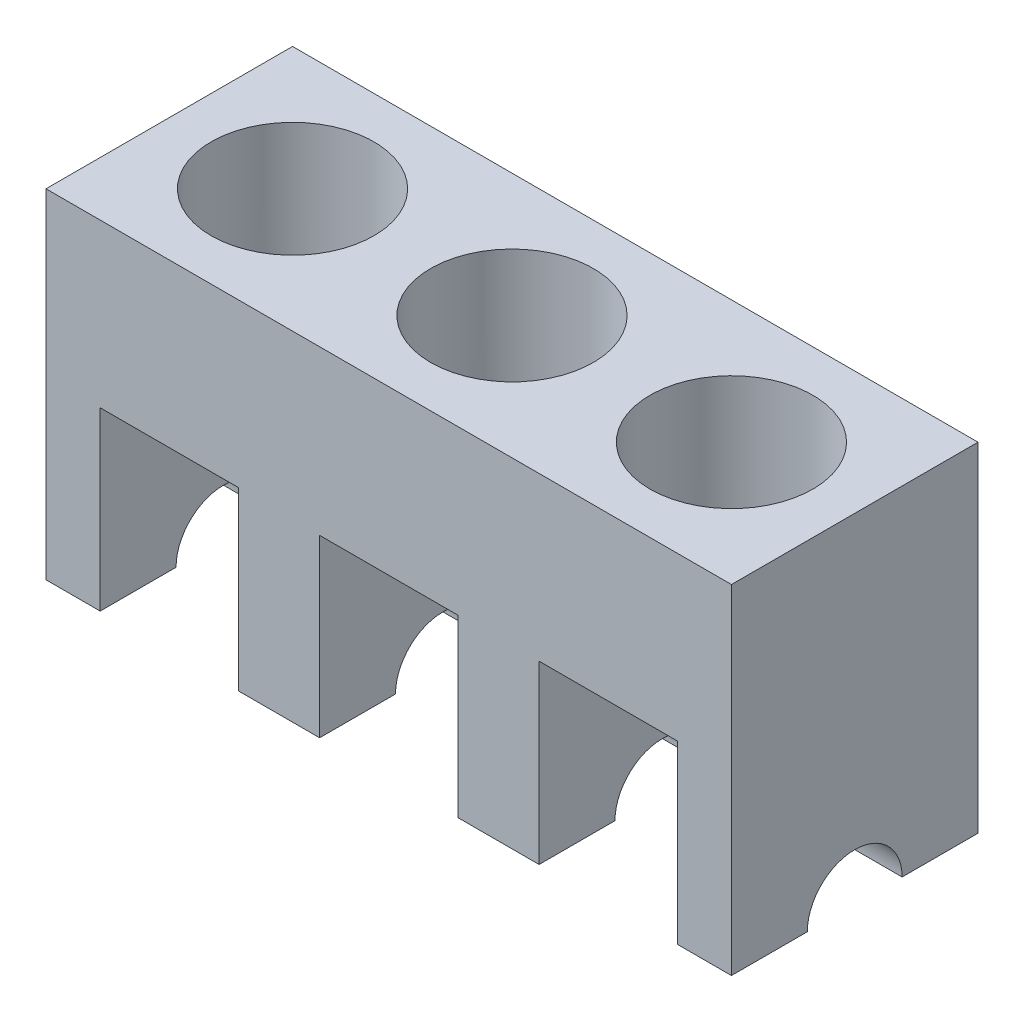
SolidWorks part; units mm, degrees
ref_plane "Front Plane" through (0, 0, 0) normal (0, 0, 1) x (1, 0, 0)
ref_plane "Top Plane" through (0, 0, 0) normal (0, 1, 0) x (1, 0, 0)
ref_plane "Right Plane" through (0, 0, 0) normal (1, 0, 0) x (0, 0, -1)
sketch "Sketch1" plane through (0, 0, 0) normal (0, 1, 0) x (1, 0, 0)
  line L0 (-56.7788, 2284.415) -> (-56.7788, -26.985)
  line L1 (-56.7788, -26.985) -> (6369.4212, -26.985)
  line L2 (6369.4212, -26.985) -> (6369.4212, 2284.415)
  line L3 (6369.4212, 2284.415) -> (-56.7788, 2284.415)
  dimension "D1" = 6426.2
  dimension "D2" = 2311.4
extrude "Boss-Extrude1" add sketch "Sketch1" along normal blind 3175
sketch "Sketch2" plane through (0, 3175, 0) normal (0, 1, 0) x (1, 0, 0)
  line L0 (-56.7788, 2284.415) -> (-56.7788, -26.985) construction
  line L1 (6369.4212, 2284.415) -> (-56.7788, 2284.415) construction
  line L3 (1098.9212, 1128.715) -> (8216.5621, 1128.715) construction
  line L4 (-56.7788, -26.985) -> (6369.4212, -26.985) construction
  circle A0 centre (1098.9212, 1128.715) radius 763.27
  circle A1 centre (3156.3212, 1128.715) radius 763.27
  circle A2 centre (5213.7212, 1128.715) radius 763.27
  dimension "D1" = 1155.7
  dimension "D3" = 1526.54
  dimension "D2" = 1155.7
  dimension "D4" = 1155.7
  dimension "D5" = 2057.4
  dimension "D6" = 1155.7
  dimension "D7" = 2057.4
extrude "Cut-Extrude1" cut sketch "Sketch2" against normal offset from surface (2057.4 mm away) 2057.4 up to face at (3156.3212, 3175, -1128.715)
sketch "Sketch6" plane through (0, 0, 0) normal (0, 0, 1) x (1, 0, 0)
  line L5 (2508.6212, -7.1583) -> (3804.0212, -7.1583)
  line L6 (2508.6212, -7.1583) -> (2508.6212, 1643.8417)
  line L7 (2508.6212, 1643.8417) -> (3804.0212, 1643.8417)
  line L8 (3804.0212, -7.1583) -> (3804.0212, 1643.8417)
  line L9 (4566.0212, 0) -> (5861.4212, 0)
  line L10 (4566.0212, 0) -> (4566.0212, 1651)
  line L11 (4566.0212, 1651) -> (5861.4212, 1651)
  line L12 (5861.4212, 0) -> (5861.4212, 1651)
  line L13 (6369.4212, 3175) -> (6369.4212, 0) construction
  line L18 (451.2212, 0) -> (1746.6212, 0)
  line L19 (451.2212, 0) -> (451.2212, 1651)
  line L20 (451.2212, 1651) -> (1746.6212, 1651)
  line L21 (1746.6212, 0) -> (1746.6212, 1651)
  line L22 (-56.7788, 3175) -> (-56.7788, 0) construction
  line L23 (-56.7788, 0) -> (6369.4212, 0) construction
  dimension "D1" = 508
  dimension "D2" = 1651
  dimension "D3" = 0
  dimension "D4" = 762
  dimension "D5" = 508
  dimension "D6" = 0
  dimension "D7" = 1651
extrude "Cut-Extrude3" cut sketch "Sketch6" against normal through all both and the other way through all
sketch "Sketch7" plane through (6369.4212, 0, 0) normal (1, 0, 0) x (0, 0, -1)
  line L0 (1128.715, 3175) -> (1128.715, -635.9583) construction
  line L1 (-26.985, 3175) -> (2284.415, 3175) construction
  line L2 (-26.985, 0) -> (2284.415, 0) construction
  circle A0 centre (1128.715, 0) radius 444.5
extrude "Cut-Extrude4" cut sketch "Sketch7" against normal through all both and the other way through all
scale "Scale1" scale about origin uniform scaling yes scale factor 0.03937
